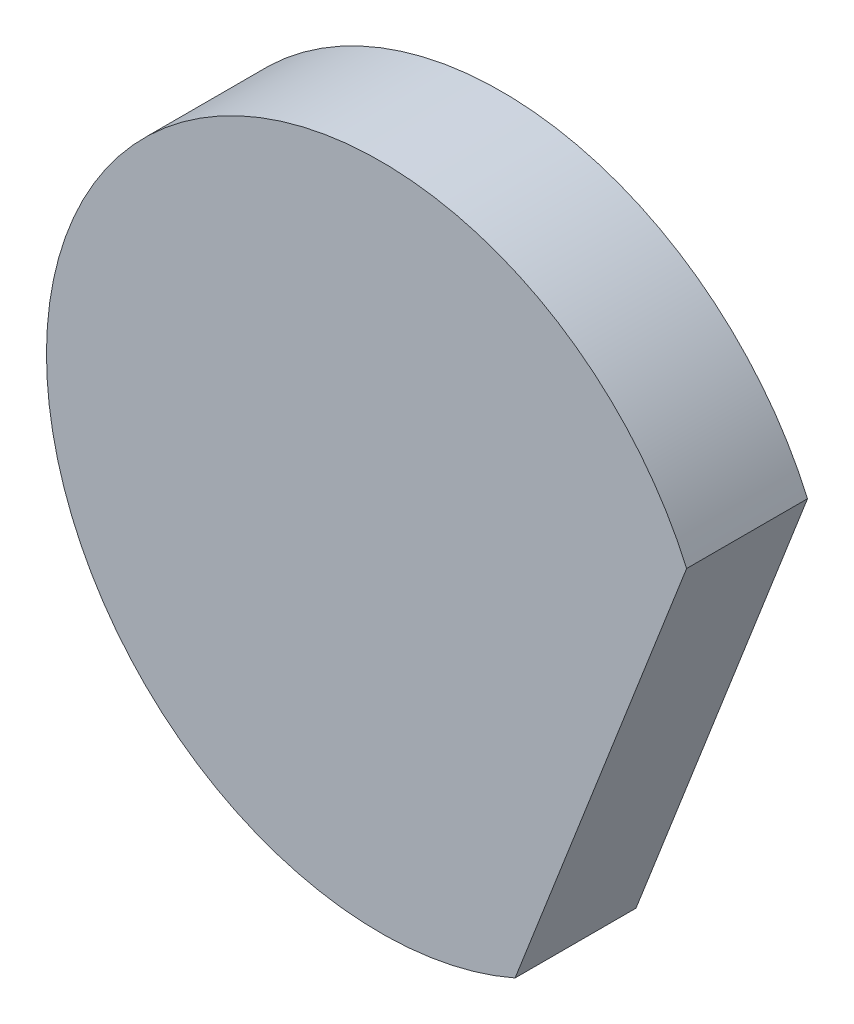
SolidWorks part; units mm, degrees
ref_plane "Front Plane" through (0, 0, 0) normal (0, 0, 1) x (1, 0, 0)
ref_plane "Top Plane" through (0, 0, 0) normal (0, 1, 0) x (1, 0, 0)
ref_plane "Right Plane" through (0, 0, 0) normal (1, 0, 0) x (0, 0, -1)
sketch "CurveSketch" plane through (0, 0, 0) normal (0, 0, 1) x (1, 0, 0)
  line L0 (2.7998, -4.3453) -> (12.9273, 21.6558)
  arc A0 (12.9273, 21.6558) -> (2.7998, -4.3453) centre (-5.137, 13.719) ccw
  dimension "D1" = 19.731
extrude "CurveBoss" add sketch "CurveSketch" along normal blind 7.139
